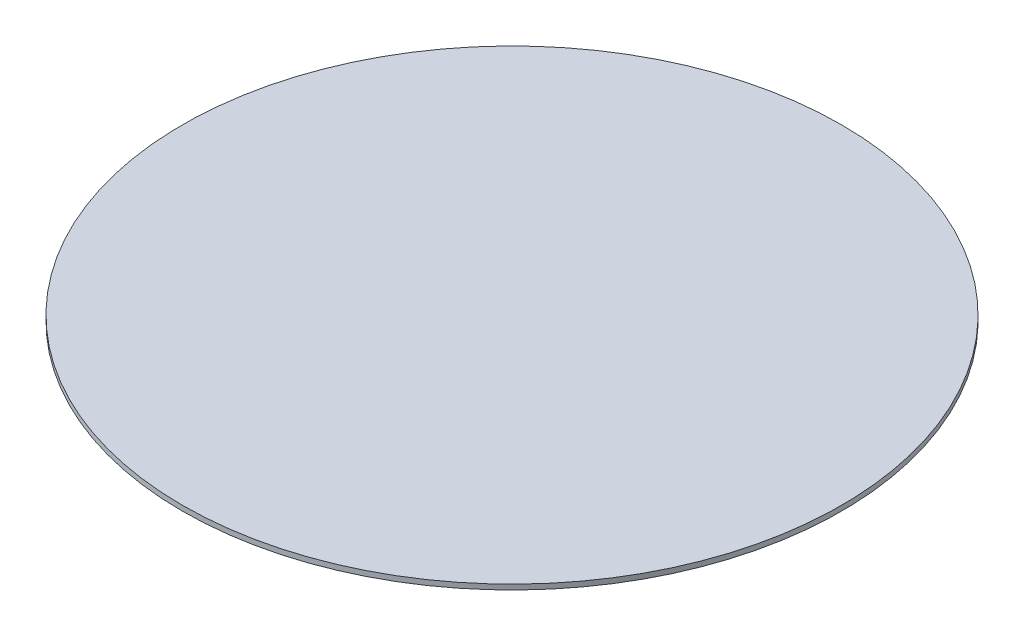
SolidWorks part; units mm, degrees
ref_plane "Plan de face" through (0, 0, 0) normal (0, 0, 1) x (1, 0, 0)
ref_plane "Plan de dessus" through (0, 0, 0) normal (0, 1, 0) x (1, 0, 0)
ref_plane "Plan de droite" through (0, 0, 0) normal (1, 0, 0) x (0, 0, -1)
sketch "Esquisse1" plane through (0, 0, 0) normal (0, 1, 0) x (1, 0, 0)
  circle A0 centre (0, 0) radius 100
  dimension "D1" = 200
extrude "Boss.-Extru.1" add sketch "Esquisse1" along normal blind 1.55
